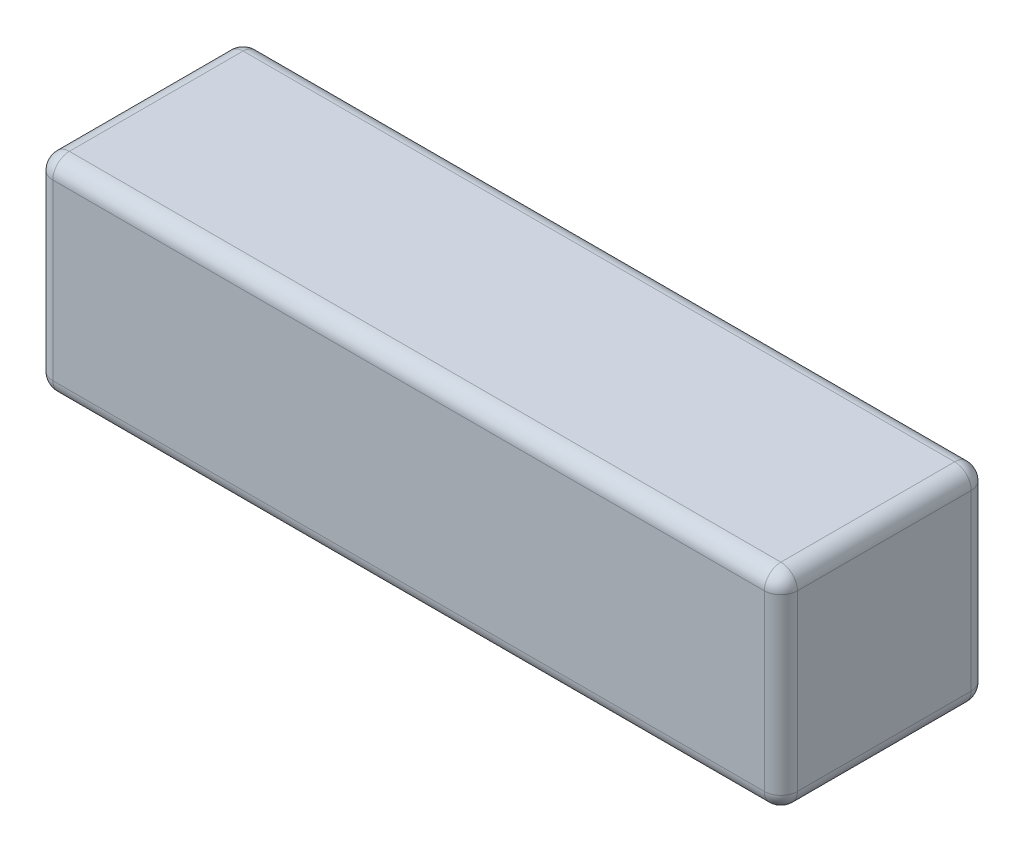
SolidWorks part; units mm, degrees
ref_plane "Front Plane" through (0, 0, 0) normal (0, 0, 1) x (1, 0, 0)
ref_plane "Top Plane" through (0, 0, 0) normal (0, 1, 0) x (1, 0, 0)
ref_plane "Right Plane" through (0, 0, 0) normal (1, 0, 0) x (0, 0, -1)
sketch "Sketch1" plane through (0, 0, 0) normal (1, 0, 0) x (0, 0, -1)
  line L1 (-12.5, 12.5) -> (12.5, 12.5)
  line L2 (-12.5, 12.5) -> (-12.5, -12.5)
  line L3 (-12.5, -12.5) -> (12.5, -12.5)
  line L4 (12.5, 12.5) -> (12.5, -12.5)
  line L5 (-12.5, 12.5) -> (12.5, -12.5) construction
  line L6 (-12.5, -12.5) -> (12.5, 12.5) construction
  point P0 (0, 0)
  dimension "D1" = 25
  dimension "D2" = 25
extrude "Boss-Extrude1" add sketch "Sketch1" along normal blind 90
fillet "Fillet1" radius 2 12 edges at (45, -12.5, -12.5) (0, -12.5, 0) (0, 0, -12.5) (0, 12.5, 0) (0, 0, 12.5) (45, -12.5, 12.5) (90, 0, -12.5) (90, 0, 12.5) (90, -12.5, 0) (90, 12.5, 0) (45, 12.5, -12.5) (45, 12.5, 12.5)
